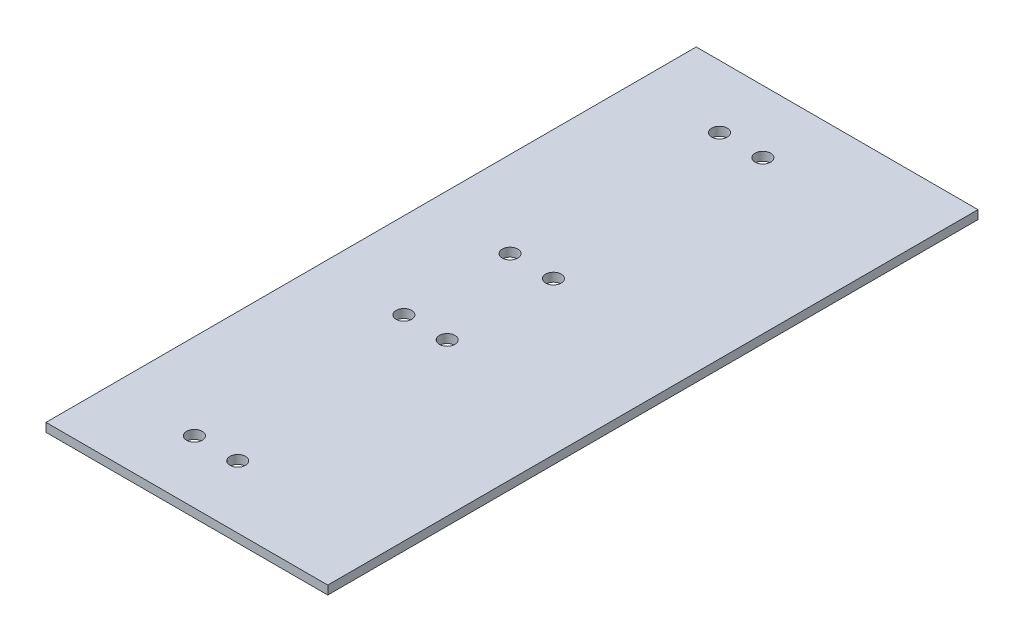
SolidWorks part; units mm, degrees
ref_plane "Alzado" through (0, 0, 0) normal (0, 0, 1) x (1, 0, 0)
ref_plane "Planta" through (0, 0, 0) normal (0, 1, 0) x (1, 0, 0)
ref_plane "Vista lateral" through (0, 0, 0) normal (1, 0, 0) x (0, 0, -1)
sketch "Croquis1" plane through (0, 0, 0) normal (0, 1, 0) x (1, 0, 0)
  line L0 (32.5, 12.25) -> (-32.5, 12.25) construction
  line L1 (32.5, 75) -> (-32.5, 75)
  line L2 (32.5, 75) -> (32.5, -75)
  line L3 (32.5, -75) -> (-32.5, -75)
  line L4 (-32.5, 75) -> (-32.5, -75)
  line L5 (32.5, 75) -> (-32.5, -75) construction
  line L6 (32.5, -75) -> (-32.5, 75) construction
  line L7 (32.5, 0) -> (-32.5, 0) construction
  line L8 (32.5, 60.57) -> (-32.5, 60.57) construction
  line L9 (-2.7, 12.25) -> (-2.7, 60.57) construction
  line L10 (-12.7, 12.25) -> (-12.7, 60.57) construction
  circle A0 centre (-2.7, 12.25) radius 1.8
  circle A1 centre (-2.7, 60.57) radius 1.8
  circle A2 centre (-12.7, -60.57) radius 1.8
  circle A3 centre (-2.7, -60.57) radius 1.8
  circle A4 centre (-12.7, 12.25) radius 1.8
  circle A5 centre (-12.7, 60.57) radius 1.8
  circle A6 centre (-12.7, -12.25) radius 1.8
  circle A7 centre (-2.7, -12.25) radius 1.8
  point P0 (0, 0)
  point P1 (0, 0)
  dimension "D3" = 10
  dimension "D4" = 3.6
  dimension "D5" = 19.8
  dimension "D1" = 150
  dimension "D2" = 65
  dimension "D6" = 48.32
  dimension "D8" = 12.25
extrude "Saliente-Extruir1" add sketch "Croquis1" along normal blind 2
